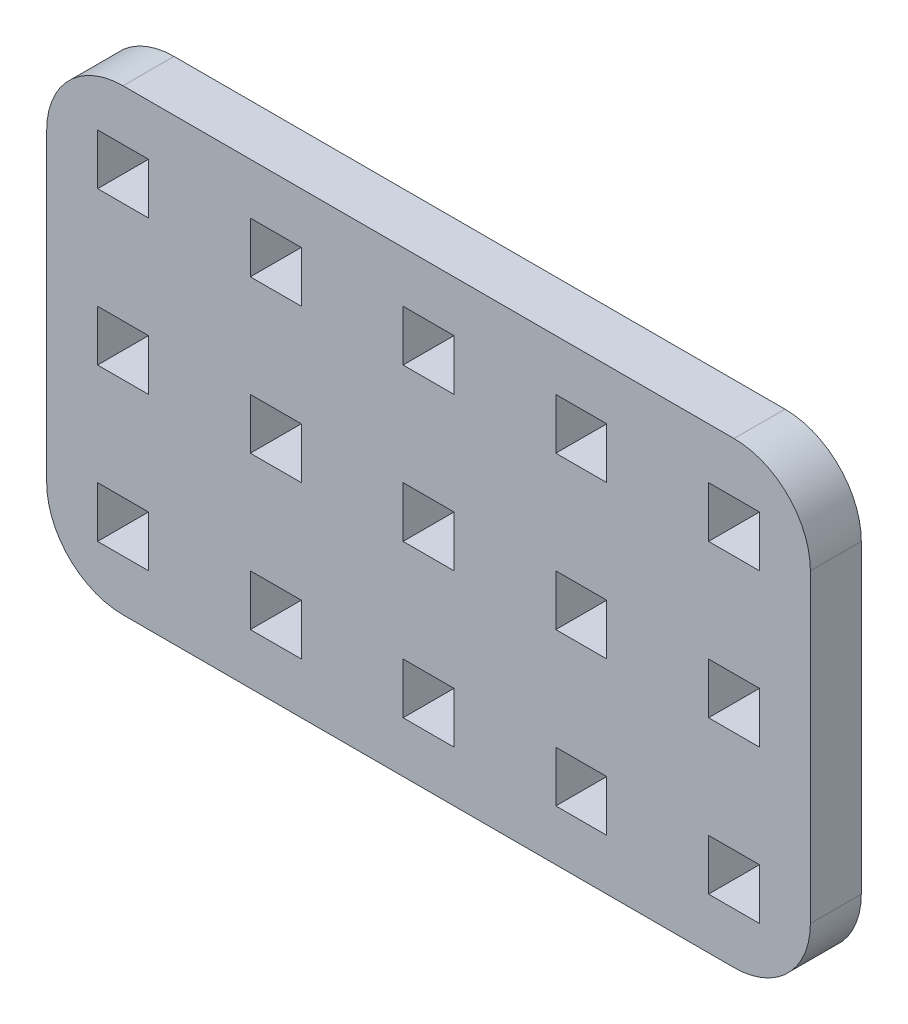
SolidWorks part; units mm, degrees
ref_plane "Alzado" through (0, 0, 0) normal (0, 0, 1) x (1, 0, 0)
ref_plane "Planta" through (0, 0, 0) normal (0, 1, 0) x (1, 0, 0)
ref_plane "Vista lateral" through (0, 0, 0) normal (1, 0, 0) x (0, 0, -1)
sketch "Model" plane through (0, 0, 0) normal (0, 0, 1) x (1, 0, 0)
  line L0 (11.1393, 296.0281) -> (11.1393, 293.0281)
  line L1 (14.1393, 296.0281) -> (11.1393, 296.0281)
  line L2 (14.1393, 293.0281) -> (14.1393, 296.0281)
  line L3 (11.1393, 293.0281) -> (14.1393, 293.0281)
  line L4 (20.1393, 296.0281) -> (20.1393, 293.0281)
  line L5 (23.1393, 296.0281) -> (20.1393, 296.0281)
  line L6 (23.1393, 293.0281) -> (23.1393, 296.0281)
  line L7 (20.1393, 293.0281) -> (23.1393, 293.0281)
  line L8 (29.1393, 296.0281) -> (29.1393, 293.0281)
  line L9 (32.1393, 296.0281) -> (29.1393, 296.0281)
  line L10 (32.1393, 293.0281) -> (32.1393, 296.0281)
  line L11 (29.1393, 293.0281) -> (32.1393, 293.0281)
  line L12 (38.1393, 296.0281) -> (38.1393, 293.0281)
  line L13 (41.1393, 296.0281) -> (38.1393, 296.0281)
  line L14 (41.1393, 293.0281) -> (41.1393, 296.0281)
  line L15 (38.1393, 293.0281) -> (41.1393, 293.0281)
  line L16 (47.1393, 296.0281) -> (47.1393, 293.0281)
  line L17 (50.1393, 296.0281) -> (47.1393, 296.0281)
  line L18 (50.1393, 293.0281) -> (50.1393, 296.0281)
  line L19 (47.1393, 293.0281) -> (50.1393, 293.0281)
  line L20 (11.1393, 278.0281) -> (11.1393, 275.0281)
  line L21 (14.1393, 278.0281) -> (11.1393, 278.0281)
  line L22 (14.1393, 275.0281) -> (14.1393, 278.0281)
  line L23 (11.1393, 275.0281) -> (14.1393, 275.0281)
  line L24 (20.1393, 278.0281) -> (20.1393, 275.0281)
  line L25 (23.1393, 278.0281) -> (20.1393, 278.0281)
  line L26 (23.1393, 275.0281) -> (23.1393, 278.0281)
  line L27 (20.1393, 275.0281) -> (23.1393, 275.0281)
  line L28 (29.1393, 278.0281) -> (29.1393, 275.0281)
  line L29 (32.1393, 278.0281) -> (29.1393, 278.0281)
  line L30 (32.1393, 275.0281) -> (32.1393, 278.0281)
  line L31 (29.1393, 275.0281) -> (32.1393, 275.0281)
  line L32 (38.1393, 278.0281) -> (38.1393, 275.0281)
  line L33 (41.1393, 278.0281) -> (38.1393, 278.0281)
  line L34 (41.1393, 275.0281) -> (41.1393, 278.0281)
  line L35 (38.1393, 275.0281) -> (41.1393, 275.0281)
  line L36 (47.1393, 278.0281) -> (47.1393, 275.0281)
  line L37 (50.1393, 278.0281) -> (47.1393, 278.0281)
  line L38 (50.1393, 275.0281) -> (50.1393, 278.0281)
  line L39 (47.1393, 275.0281) -> (50.1393, 275.0281)
  line L40 (11.1393, 287.0281) -> (11.1393, 284.0281)
  line L41 (14.1393, 287.0281) -> (11.1393, 287.0281)
  line L42 (14.1393, 284.0281) -> (14.1393, 287.0281)
  line L43 (11.1393, 284.0281) -> (14.1393, 284.0281)
  line L44 (20.1393, 287.0281) -> (20.1393, 284.0281)
  line L45 (23.1393, 287.0281) -> (20.1393, 287.0281)
  line L46 (23.1393, 284.0281) -> (23.1393, 287.0281)
  line L47 (20.1393, 284.0281) -> (23.1393, 284.0281)
  line L48 (29.1393, 287.0281) -> (29.1393, 284.0281)
  line L49 (32.1393, 287.0281) -> (29.1393, 287.0281)
  line L50 (32.1393, 284.0281) -> (32.1393, 287.0281)
  line L51 (29.1393, 284.0281) -> (32.1393, 284.0281)
  line L52 (38.1393, 287.0281) -> (38.1393, 284.0281)
  line L53 (41.1393, 287.0281) -> (38.1393, 287.0281)
  line L54 (41.1393, 284.0281) -> (41.1393, 287.0281)
  line L55 (38.1393, 284.0281) -> (41.1393, 284.0281)
  line L56 (47.1393, 287.0281) -> (47.1393, 284.0281)
  line L57 (50.1393, 287.0281) -> (47.1393, 287.0281)
  line L58 (50.1393, 284.0281) -> (50.1393, 287.0281)
  line L59 (47.1393, 284.0281) -> (50.1393, 284.0281)
  line L60 (12.6393, 299.0281) -> (48.6393, 299.0281)
  line L61 (12.6393, 272.0281) -> (48.6393, 272.0281)
  line L62 (8.1393, 294.5281) -> (8.1393, 276.5281)
  line L63 (53.1393, 294.5281) -> (53.1393, 276.5281)
  arc A0 (53.1393, 294.5281) -> (48.6393, 299.0281) centre (48.6393, 294.5281) ccw
  arc A1 (48.6393, 272.0281) -> (53.1393, 276.5281) centre (48.6393, 276.5281) ccw
  arc A2 (12.6393, 299.0281) -> (8.1393, 294.5281) centre (12.6393, 294.5281) ccw
  arc A3 (8.1393, 276.5281) -> (12.6393, 272.0281) centre (12.6393, 276.5281) ccw
extrude "Saliente-Extruir1" add sketch "Model" along normal blind 3
